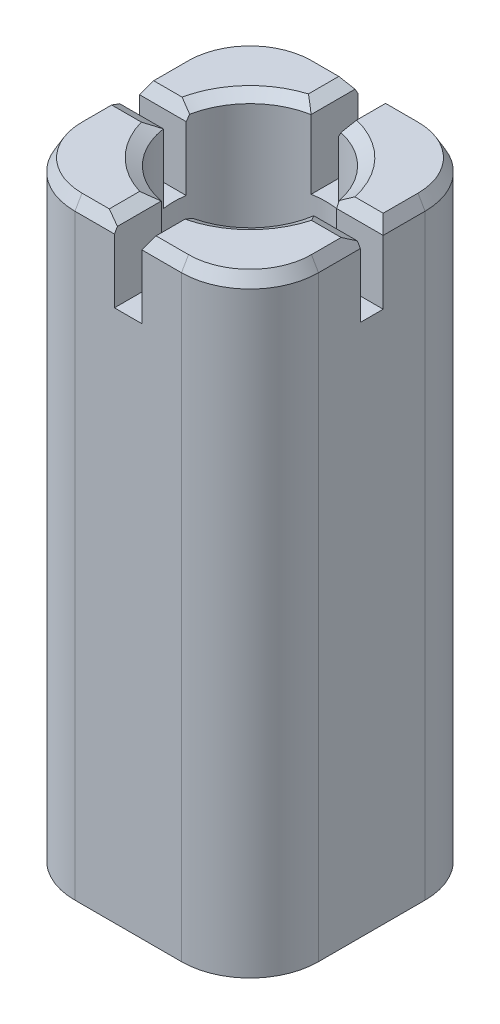
SolidWorks part; units mm, degrees
ref_plane "Front Plane" through (0, 0, 0) normal (0, 0, 1) x (1, 0, 0)
ref_plane "Top Plane" through (0, 0, 0) normal (0, 1, 0) x (1, 0, 0)
ref_plane "Right Plane" through (0, 0, 0) normal (1, 0, 0) x (0, 0, -1)
sketch "Sketch1" plane through (0, 0, 0) normal (0, 1, 0) x (1, 0, 0)
  line L1 (-8, 8) -> (8, 8)
  line L2 (-8, 8) -> (-8, -8)
  line L3 (-8, -8) -> (8, -8)
  line L4 (8, 8) -> (8, -8)
  line L5 (-8, 8) -> (8, -8) construction
  line L6 (-8, -8) -> (8, 8) construction
  circle A0 centre (0, 0) radius 5
  point P0 (0, 0)
  dimension "D1" = 16
  dimension "D2" = 16
extrude "Boss-Extrude1" add sketch "Sketch1" along normal blind 40
fillet "Fillet1" radius 4.5 4 edges at (-8, 20, -8) (-8, 20, 8) (8, 20, 8) (8, 20, -8)
sketch "Sketch2" plane through (0, 40, 0) normal (0, 1, 0) x (1, 0, 0)
  line L0 (8, -3.5) -> (8, 3.5) construction
  line L1 (-8, -0.75) -> (8, -0.75)
  line L2 (-8, -0.75) -> (-8, 0.75)
  line L3 (-8, 0.75) -> (8, 0.75)
  line L4 (8, -0.75) -> (8, 0.75)
  line L5 (-8, -0.75) -> (8, 0.75) construction
  line L6 (-8, 0.75) -> (8, -0.75) construction
  line L7 (-3.5, -8) -> (3.5, -8) construction
  line L8 (-0.9047, 8) -> (0.9047, 8)
  line L9 (-0.9047, 8) -> (-0.9047, -8)
  line L10 (-0.9047, -8) -> (0.9047, -8)
  line L11 (0.9047, 8) -> (0.9047, -8)
  line L12 (-0.9047, 8) -> (0.9047, -8) construction
  line L13 (-0.9047, -8) -> (0.9047, 8) construction
  point P0 (0, 0)
  point P8 (0, 0)
  line M1 (3.5, 8) -> (-3.5, 8)
  line M3 (-8, 3.5) -> (-8, -3.5)
  line M5 (-3.5, -8) -> (3.5, -8)
  line M7 (8, -3.5) -> (8, 3.5)
  circle M9 centre (0, 0) radius 5
extrude "Cut-Extrude1" cut sketch "Sketch2" against normal blind 5 contours L3 L1 M9 M7 | L11 L9 M1 M9 | L11 L9 M9 M5 | L3 L1 M3 M9
chamfer "Chamfer1" distance 0.8 angle 30 8 edges at (6.4717, 40, 0.75) (6.4717, 40, -0.75) (-6.4717, 40, -0.75) (-6.4717, 40, 0.75) (-0.9047, 40, 6.4587) (0.9047, 40, 6.4587) (0.9047, 40, -6.4587) (-0.9047, 40, -6.4587)
chamfer "Chamfer2" distance 0.8 angle 30 16 edges at (-3.5929, 40, 3.4772) (3.4671, 40, 3.6027) (3.5917, 40, -3.4785) (-3.713, 40, -3.3486) (-2.6024, 40, -8) (-8, 40, -2.3559) (-6.682, 40, -6.682) (-8, 40, 2.525) (-2.6024, 40, 8) (-6.682, 40, 6.682) (2.4333, 40, 8) (8, 40, 2.525) (6.682, 40, 6.682) (8, 40, -2.3559) (2.4333, 40, -8) (6.682, 40, -6.682)
sketch "Sketch3" plane through (0, 0, 0) normal (0, -1, 0) x (1, 0, 0)
  circle A0 centre (0, 0) radius 5
  circle A1 centre (0, 0) radius 4.5
extrude "Boss-Extrude2" add sketch "Sketch3" against normal blind 15
sketch "Sketch4" plane through (0, 0, 0) normal (0, -1, 0) x (1, 0, 0)
  circle A0 centre (0, 0) radius 7.25
extrude "Cut-Extrude2" cut sketch "Sketch4" against normal blind 2
